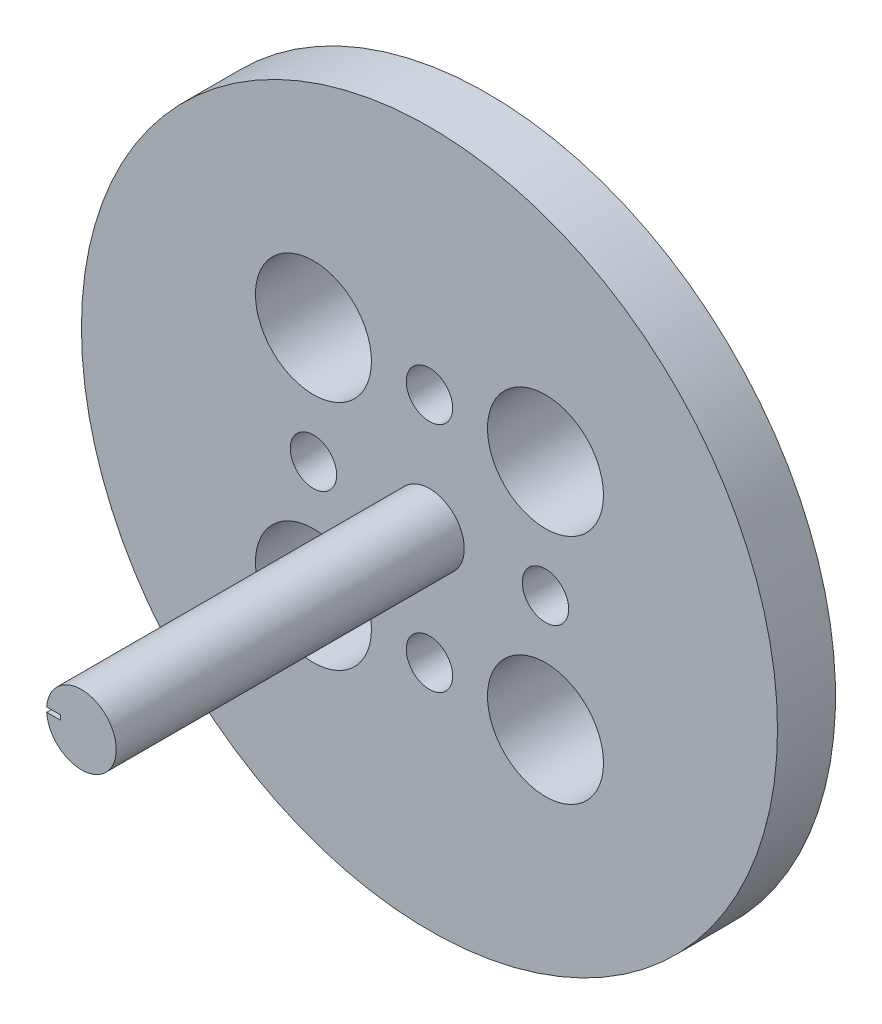
SolidWorks part; units mm, degrees
ref_plane "Front Plane" through (0, 0, 0) normal (0, 0, 1) x (1, 0, 0)
ref_plane "Top Plane" through (0, 0, 0) normal (0, 1, 0) x (1, 0, 0)
ref_plane "Right Plane" through (0, 0, 0) normal (1, 0, 0) x (0, 0, -1)
sketch "Sketch1" plane through (0, 0, 0) normal (0, 0, 1) x (1, 0, 0)
  circle A0 centre (0, 0) radius 15
  dimension "D1" = 30
extrude "body" add sketch "Sketch1" along normal blind 5 contours A0
sketch "Sketch2" plane through (0, 0, 0) normal (0, 0, -1) x (-1, 0, 0)
  circle A0 centre (0, 0) radius 15
  circle A1 centre (0, 0) radius 10
  circle A2 centre (0, 0) radius 15 construction
  dimension "D1" = 5
extrude "slew bearing lip" cut sketch "Sketch2" against normal blind 2.5
sketch "Sketch3" plane through (0, 0, 5) normal (0, 0, 1) x (1, 0, 0)
  circle A0 centre (-5, 5) radius 2.5
  circle A1 centre (5, 5) radius 2.5
  circle A2 centre (5, -5) radius 2.5
  circle A3 centre (-5, -5) radius 2.5
  dimension "D1" = 5
  dimension "D2" = 5
  dimension "D3" = 5
  dimension "D5" = 5
  dimension "D4" = 4
extrude "Cut-Extrude2" cut sketch "Sketch3" against normal through all
sketch "Sketch4" plane through (0, 0, 0) normal (0, 0, -1) x (-1, 0, 0)
  line L1 (2.6097, 0.1) -> (0.901, 0.1)
  line L2 (2.6097, 0.1) -> (2.6097, -0.1)
  line L3 (2.6097, -0.1) -> (0.901, -0.1)
  line L4 (0.901, 0.1) -> (0.901, -0.1)
  circle A0 centre (0, 0) radius 1.5
  point P7 (0.901, 0)
  point P8 (2.6097, 0.084)
  dimension "D1" = 3
  dimension "D2" = 0.2
extrude "Boss-Extrude1" add sketch "Sketch4" against normal blind 20 contours L1 A0 L3 L4
sketch "Sketch5" plane through (0, 0, 0) normal (0, 0, -1) x (-1, 0, 0)
  circle A0 centre (0, 5) radius 1
  circle A1 centre (5, 0) radius 1
  circle A2 centre (0, -5) radius 1
  circle A3 centre (-5, 0) radius 1
  point P2 (0, 0)
  point P4 (0, 0)
  dimension "D1" = 2
  dimension "D2" = 5
  dimension "D3" = 4
extrude "Cut-Extrude3" cut sketch "Sketch5" against normal through all
